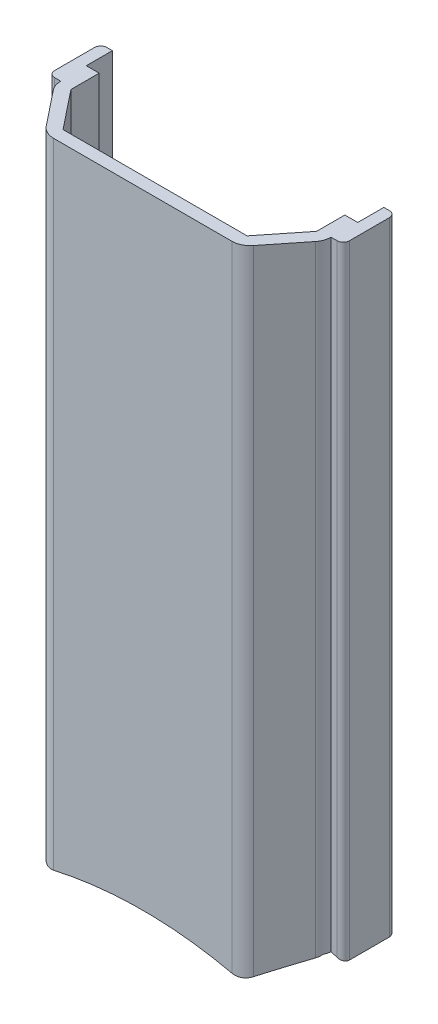
SolidWorks part; units mm, degrees
ref_plane "前视基准面" through (0, 0, 0) normal (0, 0, 1) x (1, 0, 0)
ref_plane "上视基准面" through (0, 0, 0) normal (0, 1, 0) x (1, 0, 0)
ref_plane "右视基准面" through (0, 0, 0) normal (1, 0, 0) x (0, 0, -1)
other "Configuration Table"
sketch "草图1" plane through (0, 0, 0) normal (0, 1, 0) x (1, 0, 0)
  line L5 (21.3466, -10.7196) -> (16.852, -16.3628)
  line L7 (20, -4.6001) -> (22, -4.6001)
  line L9 (20, -9.2001) -> (20, -4.6001)
  line L10 (14.9873, -15.4937) -> (20, -9.2001)
  line L11 (14.5054, -17.4937) -> (-14.5054, -17.4937)
  line L12 (-14.9873, -15.4937) -> (14.9873, -15.4937)
  line L14 (-20, -9.2001) -> (-14.9873, -15.4937)
  line L15 (-20, -4.6001) -> (-20, -9.2001)
  line L17 (-22.1, -0.3496) -> (-23, -0.3496)
  line L18 (-24, -1.3496) -> (-24, -7.8505)
  line L20 (-22, -4.6001) -> (-22.1, -4.6001)
  line L21 (-22.1, -4.6001) -> (-22.1, -0.3496)
  line L22 (22.1, -0.3496) -> (23, -0.3496)
  line L23 (24, -1.3496) -> (24, -7.8505)
  line L41 (22, -4.6001) -> (22.1, -4.6001)
  line L42 (22.1, -4.6001) -> (22.1, -0.3496)
  line L43 (-16.852, -16.3628) -> (-21.3466, -10.7196)
  line L57 (-22, -4.6001) -> (-20, -4.6001)
  line L59 (-22, -8.8505) -> (-23, -8.8505)
  line L61 (22, -8.8505) -> (23, -8.8505)
  arc A2 (23, -8.8505) -> (24, -7.8505) centre (23, -7.8505) ccw
  arc A3 (24, -1.3496) -> (23, -0.3496) centre (23, -1.3496) ccw
  arc A12 (16.852, -16.3628) -> (14.5054, -17.4937) centre (14.5054, -14.4937) cw
  arc A14 (-14.5054, -17.4937) -> (-16.852, -16.3628) centre (-14.5054, -14.4937) cw
  arc A16 (-23, -8.8505) -> (-24, -7.8505) centre (-23, -7.8505) cw
  arc A17 (-23, -0.3496) -> (-24, -1.3496) centre (-23, -1.3496) ccw
  arc A19 (21.3466, -10.7196) -> (22, -8.8505) centre (19, -8.8505) ccw
  arc A20 (-22, -8.8505) -> (-21.3466, -10.7196) centre (-19, -8.8505) ccw
  dimension "D3" = 0.1
  dimension "D2" = 0.1
extrude "凸台-拉伸1" add sketch "草图1" along normal up to surface (58.8974 mm away)
sketch "草图2" plane through (0, 0, 0) normal (0, -1, 0) x (1, 0, 0)
  line L18 (23, 8.8505) -> (22, 8.8505)
  line L19 (-24, 7.8505) -> (-24, 1.3496)
  line L20 (-23, 0.3496) -> (-22.1, 0.3496)
  line L21 (-22.1, 0.3496) -> (-22.1, 4.6001)
  line L22 (-22.1, 4.6001) -> (-20, 4.6001)
  line L23 (-20, 4.6001) -> (-20, 9.2001)
  line L24 (-20, 9.2001) -> (-14.9873, 15.4937)
  line L25 (-14.9873, 15.4937) -> (14.9873, 15.4937)
  line L26 (14.9873, 15.4937) -> (20, 9.2001)
  line L27 (20, 9.2001) -> (20, 4.6001)
  line L28 (20, 4.6001) -> (22.1, 4.6001)
  line L29 (22.1, 4.6001) -> (22.1, 0.3496)
  line L30 (22.1, 0.3496) -> (23, 0.3496)
  line L31 (24, 1.3496) -> (24, 7.8505)
  line L32 (23, 8.8505) -> (22, 8.8505)
  line L33 (21.3466, 10.7196) -> (16.852, 16.3628)
  line L34 (14.5054, 17.4937) -> (-14.5054, 17.4937)
  line L37 (-24, 7.8505) -> (-24, 1.3496)
  line L38 (-23, 0.3496) -> (-22.1, 0.3496)
  line L39 (-22.1, 0.3496) -> (-22.1, 4.6001)
  line L40 (-22.1, 4.6001) -> (-20, 4.6001)
  line L41 (-20, 4.6001) -> (-20, 9.2001)
  line L42 (-20, 9.2001) -> (-14.9873, 15.4937)
  line L43 (-14.9873, 15.4937) -> (14.9873, 15.4937)
  line L44 (14.9873, 15.4937) -> (20, 9.2001)
  line L45 (20, 9.2001) -> (20, 4.6001)
  line L46 (20, 4.6001) -> (22.1, 4.6001)
  line L47 (22.1, 4.6001) -> (22.1, 0.3496)
  line L48 (22.1, 0.3496) -> (23, 0.3496)
  line L49 (24, 1.3496) -> (24, 7.8505)
  line L51 (21.3466, 10.7196) -> (16.852, 16.3628)
  line L52 (14.5054, 17.4937) -> (-14.5054, 17.4937)
  line L57 (-16.852, 16.3628) -> (-21.3466, 10.7196)
  line L58 (-16.852, 16.3628) -> (-21.3466, 10.7196)
  line L61 (-22, 8.8505) -> (-23, 8.8505)
  line L62 (-22, 8.8505) -> (-23, 8.8505)
  arc A8 (-21.3466, 10.7196) -> (-22, 8.8505) centre (-19, 8.8505) ccw
  arc A9 (-21.3466, 10.7196) -> (-22, 8.8505) centre (-19, 8.8505) ccw
  arc A10 (22, 8.8505) -> (21.3466, 10.7196) centre (19, 8.8505) ccw
  arc A11 (22, 8.8505) -> (21.3466, 10.7196) centre (19, 8.8505) ccw
  arc A12 (-23, 8.8505) -> (-24, 7.8505) centre (-23, 7.8505) ccw
  arc A13 (-24, 1.3496) -> (-23, 0.3496) centre (-23, 1.3496) ccw
  arc A14 (23, 0.3496) -> (24, 1.3496) centre (23, 1.3496) ccw
  arc A15 (24, 7.8505) -> (23, 8.8505) centre (23, 7.8505) ccw
  arc A18 (16.852, 16.3628) -> (14.5054, 17.4937) centre (14.5054, 14.4937) ccw
  arc A19 (-14.5054, 17.4937) -> (-16.852, 16.3628) centre (-14.5054, 14.4937) ccw
  arc A22 (-23, 8.8505) -> (-24, 7.8505) centre (-23, 7.8505) ccw
  arc A23 (-24, 1.3496) -> (-23, 0.3496) centre (-23, 1.3496) ccw
  arc A24 (23, 0.3496) -> (24, 1.3496) centre (23, 1.3496) ccw
  arc A25 (24, 7.8505) -> (23, 8.8505) centre (23, 7.8505) ccw
  arc A28 (16.852, 16.3628) -> (14.5054, 17.4937) centre (14.5054, 14.4937) ccw
  arc A29 (-14.5054, 17.4937) -> (-16.852, 16.3628) centre (-14.5054, 14.4937) ccw
  dimension "D1" = 0
extrude "凸台-拉伸2" add sketch "草图2" along normal up to surface (38.3996 mm away)
ref_plane "基准面1" through (0, -38.3996, 0) normal (0, -1, 0) x (-1, 0, 0)
sketch "草图3" plane through (0, 0, 4.6001) normal (0, 0, -1) x (-1, 0, 0)
  line L0 (22.1, -38.3996) -> (22.1, -35.3996)
  line L1 (22.1, 58.8974) -> (22.1, -38.3996) construction
  line L2 (22.1, -35.3996) -> (-22.1, -35.3996)
  line L3 (-22.1, 58.8974) -> (-22.1, -38.3996) construction
  line L4 (-22.1, -35.3996) -> (-22.1, -38.3996)
  line L5 (-22.1, -38.3996) -> (22.1, -38.3996)
  dimension "D1" = 3
extrude "凸台-拉伸3" add sketch "草图3" against normal up to surface (12.8937 mm away) up to face at (0, 10.2489, 17.4937)
sketch "草图4" plane through (0, 0, 4.6001) normal (0, 0, -1) x (-1, 0, 0)
  line L0 (22.1, 38.8974) -> (-22.1, 38.8974)
  line L3 (22.1, 58.8974) -> (22.1, -38.3996) construction
  line L4 (22.1, 38.8974) -> (22.1, 35.8974)
  line L7 (-22.1, 58.8974) -> (-22.1, -38.3996) construction
  line L8 (-22.1, 38.8974) -> (-22.1, 35.8974)
  line L9 (-22.1, 35.8974) -> (22.1, 35.8974)
  dimension "D2" = 3
extrude "凸台-拉伸4" add sketch "草图4" against normal up to surface (12.8937 mm away) up to face at (0, -12.5754, 17.4937)
sketch "草图5" plane through (0, 38.8974, 0) normal (0, 1, 0) x (1, 0, 0)
  line L3 (-22, -8.8505) -> (-22.1, -8.8505)
  line L4 (-22.1, -8.8505) -> (-22.1, -17.4937)
  line L5 (-22.1, -17.4937) -> (-14.5054, -17.4937)
  line L7 (-22.1, -8.8505) -> (-22.1, -17.4937)
  line L8 (-22.1, -17.4937) -> (-14.5054, -17.4937)
  line L9 (14.5054, -17.4937) -> (22.1, -17.4937)
  line L10 (22.1, -17.4937) -> (22.1, -8.8505)
  line L11 (21.3466, -10.7196) -> (16.852, -16.3628)
  line L12 (14.5054, -17.4937) -> (22.1, -17.4937)
  line L13 (22.1, -17.4937) -> (22.1, -8.8505)
  line L14 (21.3466, -10.7196) -> (16.852, -16.3628)
  line L17 (-22, -8.8505) -> (-22.1, -8.8505)
  line L18 (-16.852, -16.3628) -> (-21.3466, -10.7196)
  line L19 (-16.852, -16.3628) -> (-21.3466, -10.7196)
  line L22 (22.1, -8.8505) -> (22, -8.8505)
  line L23 (22.1, -8.8505) -> (22, -8.8505)
  arc A2 (-22, -8.8505) -> (-21.3466, -10.7196) centre (-19, -8.8505) ccw
  arc A3 (-16.852, -16.3628) -> (-14.5054, -17.4937) centre (-14.5054, -14.4937) ccw
  arc A4 (-22, -8.8505) -> (-21.3466, -10.7196) centre (-19, -8.8505) ccw
  arc A5 (21.3466, -10.7196) -> (22, -8.8505) centre (19, -8.8505) ccw
  arc A6 (-16.852, -16.3628) -> (-14.5054, -17.4937) centre (-14.5054, -14.4937) ccw
  arc A9 (14.5054, -17.4937) -> (16.852, -16.3628) centre (14.5054, -14.4937) ccw
  arc A10 (21.3466, -10.7196) -> (22, -8.8505) centre (19, -8.8505) ccw
  arc A12 (14.5054, -17.4937) -> (16.852, -16.3628) centre (14.5054, -14.4937) ccw
  dimension "D1" = 0
  dimension "D2" = 0
extrude "切除-拉伸1" cut sketch "草图5" against normal up to surface (77.297 mm away) contours A6 L8 L7 L17 A4 L19 | A12 L14 A10 L23 L13 L12 up to face at (0, -38.3996, 6.2118)
sketch "草图6" plane through (0, 38.8974, 0) normal (0, 1, 0) x (1, 0, 0)
  line L4 (5.2943, -14.0001) -> (5.2943, -7.5001)
  line L5 (-5.2943, -7.5001) -> (5.2943, -7.5001)
  line L6 (-5.2943, -7.5001) -> (-5.2943, -14.0001)
  line L7 (-5.2943, -14.0001) -> (5.2943, -14.0001)
extrude "切除-拉伸2" cut sketch "草图6" against normal up to surface (3 mm away) up to face at (0, 35.8974, 9.7646)
sketch "草图7" plane through (0, -38.3996, 0) normal (0, -1, 0) x (-1, 0, 0)
  line L20 (20, -4.6001) -> (20, -9.2001)
  line L21 (22, -4.6001) -> (20, -4.6001)
  line L22 (22.1, -4.6001) -> (22, -4.6001)
  line L23 (22.1, -0.3496) -> (22.1, -4.6001)
  line L24 (23, -0.3496) -> (22.1, -0.3496)
  line L25 (24, -7.8505) -> (24, -1.3496)
  line L26 (22, -8.8505) -> (23, -8.8505)
  line L27 (16.852, -16.3628) -> (21.3466, -10.7196)
  line L28 (-14.5054, -17.4937) -> (14.5054, -17.4937)
  line L29 (-21.3466, -10.7196) -> (-16.852, -16.3628)
  line L30 (-23, -8.8505) -> (-22, -8.8505)
  line L31 (-24, -1.3496) -> (-24, -7.8505)
  line L32 (-22.1, -0.3496) -> (-23, -0.3496)
  line L33 (-22.1, -4.6001) -> (-22.1, -0.3496)
  line L34 (-22, -4.6001) -> (-22.1, -4.6001)
  line L35 (-20, -4.6001) -> (-22, -4.6001)
  line L36 (-20, -9.2001) -> (-20, -4.6001)
  line L37 (-14.9873, -15.4937) -> (-20, -9.2001)
  line L38 (14.9873, -15.4937) -> (-14.9873, -15.4937)
  line L39 (20, -9.2001) -> (14.9873, -15.4937)
  line L40 (20, -4.6001) -> (20, -9.2001)
  line L41 (22, -4.6001) -> (20, -4.6001)
  line L42 (22.1, -4.6001) -> (22, -4.6001)
  line L43 (22.1, -0.3496) -> (22.1, -4.6001)
  line L44 (23, -0.3496) -> (22.1, -0.3496)
  line L45 (24, -7.8505) -> (24, -1.3496)
  line L46 (22, -8.8505) -> (23, -8.8505)
  line L47 (16.852, -16.3628) -> (21.3466, -10.7196)
  line L48 (-14.5054, -17.4937) -> (14.5054, -17.4937)
  line L49 (-21.3466, -10.7196) -> (-16.852, -16.3628)
  line L50 (-23, -8.8505) -> (-22, -8.8505)
  line L51 (-24, -1.3496) -> (-24, -7.8505)
  line L52 (-22.1, -0.3496) -> (-23, -0.3496)
  line L53 (-22.1, -4.6001) -> (-22.1, -0.3496)
  line L54 (-22, -4.6001) -> (-22.1, -4.6001)
  line L55 (-20, -4.6001) -> (-22, -4.6001)
  line L56 (-20, -9.2001) -> (-20, -4.6001)
  line L57 (-14.9873, -15.4937) -> (-20, -9.2001)
  line L58 (14.9873, -15.4937) -> (-14.9873, -15.4937)
  line L59 (20, -9.2001) -> (14.9873, -15.4937)
  arc A8 (24, -1.3496) -> (23, -0.3496) centre (23, -1.3496) ccw
  arc A9 (23, -8.8505) -> (24, -7.8505) centre (23, -7.8505) ccw
  arc A10 (21.3466, -10.7196) -> (22, -8.8505) centre (19, -8.8505) ccw
  arc A11 (14.5054, -17.4937) -> (16.852, -16.3628) centre (14.5054, -14.4937) ccw
  arc A12 (-16.852, -16.3628) -> (-14.5054, -17.4937) centre (-14.5054, -14.4937) ccw
  arc A13 (-22, -8.8505) -> (-21.3466, -10.7196) centre (-19, -8.8505) ccw
  arc A14 (-24, -7.8505) -> (-23, -8.8505) centre (-23, -7.8505) ccw
  arc A15 (-23, -0.3496) -> (-24, -1.3496) centre (-23, -1.3496) ccw
  arc A16 (24, -1.3496) -> (23, -0.3496) centre (23, -1.3496) ccw
  arc A17 (23, -8.8505) -> (24, -7.8505) centre (23, -7.8505) ccw
  arc A18 (21.3466, -10.7196) -> (22, -8.8505) centre (19, -8.8505) ccw
  arc A19 (14.5054, -17.4937) -> (16.852, -16.3628) centre (14.5054, -14.4937) ccw
  arc A20 (-16.852, -16.3628) -> (-14.5054, -17.4937) centre (-14.5054, -14.4937) ccw
  arc A21 (-22, -8.8505) -> (-21.3466, -10.7196) centre (-19, -8.8505) ccw
  arc A22 (-24, -7.8505) -> (-23, -8.8505) centre (-23, -7.8505) ccw
  arc A23 (-23, -0.3496) -> (-24, -1.3496) centre (-23, -1.3496) ccw
  dimension "D1" = 0
extrude "凸台-拉伸5" add sketch "草图7" along normal blind 15
sketch "草图8" plane through (0, 0, 0) normal (1, 0, 0) x (0, 0, -1)
  line L14 (-9.8992, -38.2996) -> (-20.2915, -44.2996)
  line L18 (-9.8992, -40.3996) -> (-9.8992, -176.3996) construction
  line L19 (-20.2915, -44.3996) -> (-20.2915, -172.3996) construction
  line L20 (-20.2915, -44.2996) -> (-20.2915, -55.8019)
  line L21 (-9.8992, -108.3996) -> (14.8215, -108.3996) construction
  line L22 (-20.2915, -46.3996) -> (-20.2915, -170.3996) construction
  line L23 (-20.2915, -55.8019) -> (11.0914, -55.8019)
  line L25 (0.6991, -38.2996) -> (-9.8992, -38.2996)
  line L26 (-4.6001, 35.8974) -> (-4.6001, -35.3996) construction
  line L27 (11.0914, -44.2996) -> (11.0914, -55.8019)
  line L28 (0.6991, -38.2996) -> (11.0914, -44.2996)
revolve "切除-旋转1" cut sketch "草图8" angle 360 about L21
